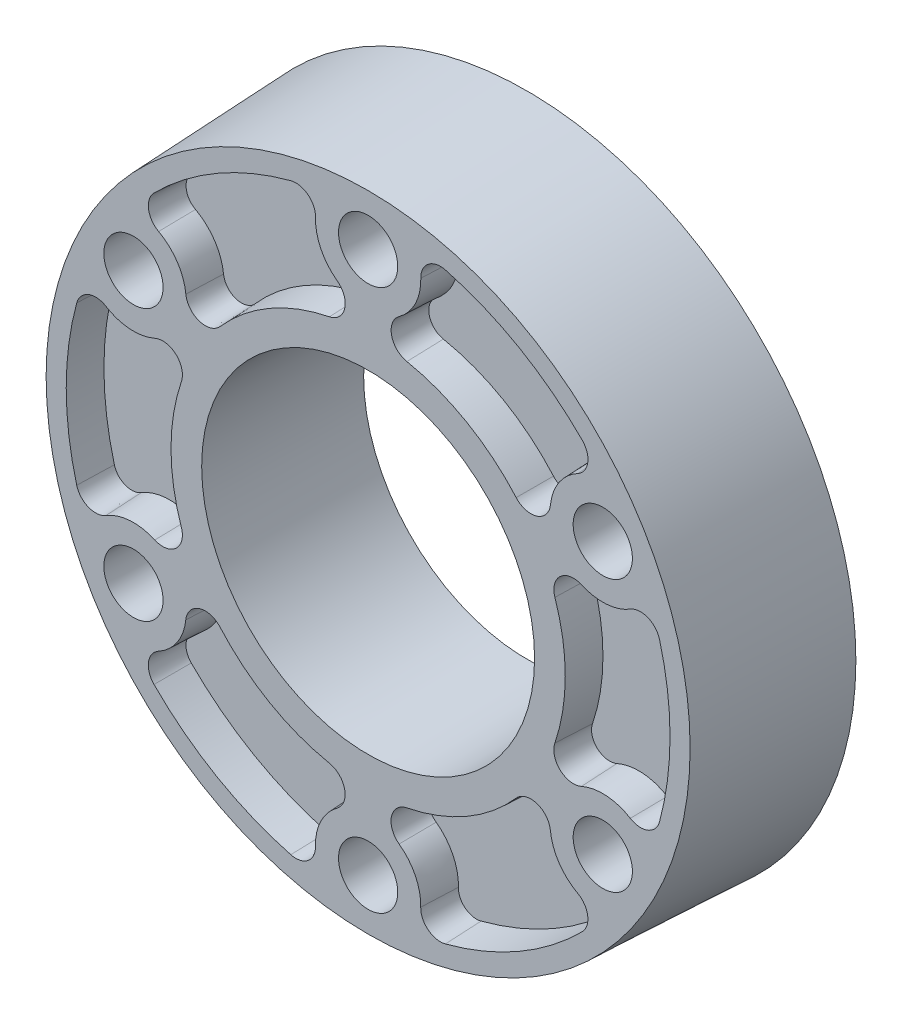
SolidWorks part; units mm, degrees
ref_plane "Front Plane" through (0, 0, 0) normal (0, 0, 1) x (1, 0, 0)
ref_plane "Top Plane" through (0, 0, 0) normal (0, 1, 0) x (1, 0, 0)
ref_plane "Right Plane" through (0, 0, 0) normal (1, 0, 0) x (0, 0, -1)
sketch "Sketch1" plane through (0, 0, 0) normal (0, 1, 0) x (1, 0, 0)
  line L0 (28.9071, 10.7817) -> (0, 10.7817)
  line L1 (0, 10.7817) -> (0, -3.175)
  line L2 (0, -3.175) -> (28.2978, -3.175)
  line L3 (28.2978, -3.175) -> (28.9071, 10.7817)
  line L4 (0, 10.7817) -> (0, -3.175) construction
revolve "Revolve1" add sketch "Sketch1" angle 360 about L4
sketch "Sketch2" plane through (0, 0, 3.175) normal (0, 0, 1) x (1, 0, 0)
  arc A0 (-18.4123, 15.9751) -> (-16.0184, 12.3998) centre (-20.6222, 11.9062) cw
  arc A1 (-16.0184, 12.3998) -> (-13.0062, 11.4436) centre (-14.3021, 12.5838) ccw
  arc A2 (-13.0062, 11.4436) -> (-3.3997, 16.987) centre (0, 0) cw
  arc A3 (-3.3997, 16.987) -> (-2.7222, 20.0749) centre (-3.7384, 18.6796) ccw
  arc A4 (-2.7222, 20.0749) -> (-4.6223, 23.9343) centre (0, 23.8125) cw
  arc A5 (-4.6223, 23.9343) -> (-6.7895, 25.6484) centre (-6.3478, 23.9797) ccw
  arc A6 (-6.7895, 25.6484) -> (-18.8124, 18.7091) centre (0, 0) ccw
  arc A7 (-18.8124, 18.7091) -> (-18.4123, 15.9751) centre (-17.5885, 17.4919) ccw
extrude "Cut-Extrude1" cut sketch "Sketch2" against normal blind 3.175 draft 2.5
sketch "Sketch3" plane through (0, 0, 3.175) normal (0, 0, 1) x (1, 0, 0)
  arc A0 (4.6287, 23.9331) -> (2.7294, 20.0722) centre (0, 23.8125) cw
  arc A1 (2.7294, 20.0722) -> (3.4074, 16.9855) centre (3.7469, 18.6779) ccw
  arc A2 (3.4074, 16.9855) -> (13.0114, 11.4377) centre (0, 0) cw
  arc A3 (13.0114, 11.4377) -> (16.0242, 12.3949) centre (14.3078, 12.5773) ccw
  arc A4 (16.0242, 12.3949) -> (18.4165, 15.9701) centre (20.6222, 11.9063) cw
  arc A5 (18.4165, 15.9701) -> (18.8174, 18.7041) centre (17.5931, 17.4872) ccw
  arc A6 (18.8174, 18.7041) -> (6.7964, 25.6466) centre (0, 0) ccw
  arc A7 (6.7964, 25.6466) -> (4.6287, 23.9331) centre (6.3542, 23.978) ccw
extrude "Cut-Extrude2" cut sketch "Sketch3" against normal blind 3.175 draft 2.5
sketch "Sketch4" plane through (0, 0, 3.175) normal (0, 0, 1) x (1, 0, 0)
  arc A0 (23.041, 7.958) -> (18.7478, 7.6724) centre (20.6222, 11.9062) cw
  arc A1 (18.7478, 7.6724) -> (16.4135, 5.5419) centre (18.049, 6.0941) ccw
  arc A2 (16.4135, 5.5419) -> (16.411, -5.5493) centre (0, 0) cw
  arc A3 (16.411, -5.5493) -> (18.7464, -7.6799) centre (18.0462, -6.1022) ccw
  arc A4 (18.7464, -7.6799) -> (23.0388, -7.9641) centre (20.6222, -11.9063) cw
  arc A5 (23.0388, -7.9641) -> (25.6069, -6.9443) centre (23.9409, -6.4925) ccw
  arc A6 (25.6069, -6.9443) -> (25.6087, 6.9375) centre (0, 0) ccw
  arc A7 (25.6087, 6.9375) -> (23.041, 7.958) centre (23.9427, 6.4861) ccw
extrude "Cut-Extrude3" cut sketch "Sketch4" against normal blind 3.175 draft 2.5
sketch "Sketch5" plane through (0, 0, 3.175) normal (0, 0, 1) x (1, 0, 0)
  arc A0 (18.4123, -15.9751) -> (16.0184, -12.3998) centre (20.6222, -11.9062) cw
  arc A1 (16.0184, -12.3998) -> (13.0062, -11.4436) centre (14.3021, -12.5838) ccw
  arc A2 (13.0062, -11.4436) -> (3.3997, -16.987) centre (0, 0) cw
  arc A3 (3.3997, -16.987) -> (2.7222, -20.0749) centre (3.7384, -18.6796) ccw
  arc A4 (2.7222, -20.0749) -> (4.6223, -23.9343) centre (0, -23.8125) cw
  arc A5 (4.6223, -23.9343) -> (6.7895, -25.6484) centre (6.3478, -23.9797) ccw
  arc A6 (6.7895, -25.6484) -> (18.8124, -18.7091) centre (0, 0) ccw
  arc A7 (18.8124, -18.7091) -> (18.4123, -15.9751) centre (17.5885, -17.4919) ccw
extrude "Cut-Extrude4" cut sketch "Sketch5" against normal blind 3.175 draft 2.5
sketch "Sketch6" plane through (0, 0, 3.175) normal (0, 0, 1) x (1, 0, 0)
  arc A0 (-4.6287, -23.9331) -> (-2.7294, -20.0722) centre (0, -23.8125) cw
  arc A1 (-2.7294, -20.0722) -> (-3.4074, -16.9855) centre (-3.7469, -18.6779) ccw
  arc A2 (-3.4074, -16.9855) -> (-13.0114, -11.4377) centre (0, 0) cw
  arc A3 (-13.0114, -11.4377) -> (-16.0242, -12.3949) centre (-14.3078, -12.5773) ccw
  arc A4 (-16.0242, -12.3949) -> (-18.4165, -15.9701) centre (-20.6222, -11.9062) cw
  arc A5 (-18.4165, -15.9701) -> (-18.8174, -18.7041) centre (-17.5931, -17.4872) ccw
  arc A6 (-18.8174, -18.7041) -> (-6.7964, -25.6466) centre (0, 0) ccw
  arc A7 (-6.7964, -25.6466) -> (-4.6287, -23.9331) centre (-6.3542, -23.978) ccw
extrude "Cut-Extrude5" cut sketch "Sketch6" against normal blind 3.175 draft 2.5
sketch "Sketch7" plane through (0, 0, 3.175) normal (0, 0, 1) x (1, 0, 0)
  arc A0 (-23.041, -7.958) -> (-18.7478, -7.6724) centre (-20.6222, -11.9062) cw
  arc A1 (-18.7478, -7.6724) -> (-16.4135, -5.5419) centre (-18.049, -6.0941) ccw
  arc A2 (-16.4135, -5.5419) -> (-16.411, 5.5493) centre (0, 0) cw
  arc A3 (-16.411, 5.5493) -> (-18.7464, 7.6799) centre (-18.0462, 6.1022) ccw
  arc A4 (-18.7464, 7.6799) -> (-23.0388, 7.9641) centre (-20.6222, 11.9063) cw
  arc A5 (-23.0388, 7.9641) -> (-25.6069, 6.9443) centre (-23.9409, 6.4925) ccw
  arc A6 (-25.6069, 6.9443) -> (-25.6087, -6.9375) centre (0, 0) ccw
  arc A7 (-25.6087, -6.9375) -> (-23.041, -7.958) centre (-23.9427, -6.4861) ccw
extrude "Cut-Extrude6" cut sketch "Sketch7" against normal blind 3.175 draft 2.5
hole_wizard "Hole1" positions "Sketch9" profile "Sketch8" legacy
sketch "Sketch9" plane through (0, 0, 3.175) normal (0, 0, 1) x (1, 0, 0)
  point P0 (20.6222, 11.9062)
  point P1 (20.6222, -11.9062)
  point P2 (0, -23.8125)
  point P3 (-20.6222, -11.9062)
sketch "Sketch8" plane through (20.6222, 11.9062, 3.175) normal (1, 0, 0) x (0, -1, 0)
  line L0 (0, 0) -> (0, 13.9567)
  line L1 (0, 13.9567) -> (2.3263, 13.9567)
  line L2 (2.3263, 13.9567) -> (2.6035, 0)
  line L3 (2.6035, 0) -> (0, 0)
  line L4 (0, 110) -> (0, -10) construction
  dimension "Minor Diameter" = 4.6525
  dimension "Depth" = 13.9567
  dimension "Major Diameter" = 5.207
hole_wizard "Hole2" positions "Sketch11" profile "Sketch10" legacy
sketch "Sketch11" plane through (0, 0, 3.175) normal (0, 0, 1) x (1, 0, 0)
  point P0 (0, 0)
sketch "Sketch10" plane through (0, 0, 3.175) normal (1, 0, 0) x (0, -1, 0)
  line L0 (0, 0) -> (0, 13.9567)
  line L1 (0, 13.9567) -> (14.351, 13.9567)
  line L2 (14.351, 13.9567) -> (14.6282, 0)
  line L3 (14.6282, 0) -> (0, 0)
  line L4 (0, 110) -> (0, -10) construction
  dimension "Minor Diameter" = 28.702
  dimension "Depth" = 13.9567
  dimension "Major Diameter" = 29.2565
hole_wizard "Hole3" positions "Sketch13" profile "Sketch12" legacy
sketch "Sketch13" plane through (0, 0, 3.175) normal (0, 0, 1) x (1, 0, 0)
  point P0 (-20.6222, 11.9062)
  point P1 (0, 23.8125)
sketch "Sketch12" plane through (-20.6222, 11.9062, 3.175) normal (1, 0, 0) x (0, -1, 0)
  line L0 (0, 0) -> (0, 13.9567)
  line L1 (0, 13.9567) -> (2.3818, 13.9567)
  line L2 (2.3818, 13.9567) -> (2.6035, 0)
  line L3 (2.6035, 0) -> (0, 0)
  line L4 (0, 110) -> (0, -10) construction
  dimension "Minor Diameter" = 4.7635
  dimension "Depth" = 13.9567
  dimension "Major Diameter" = 5.207
